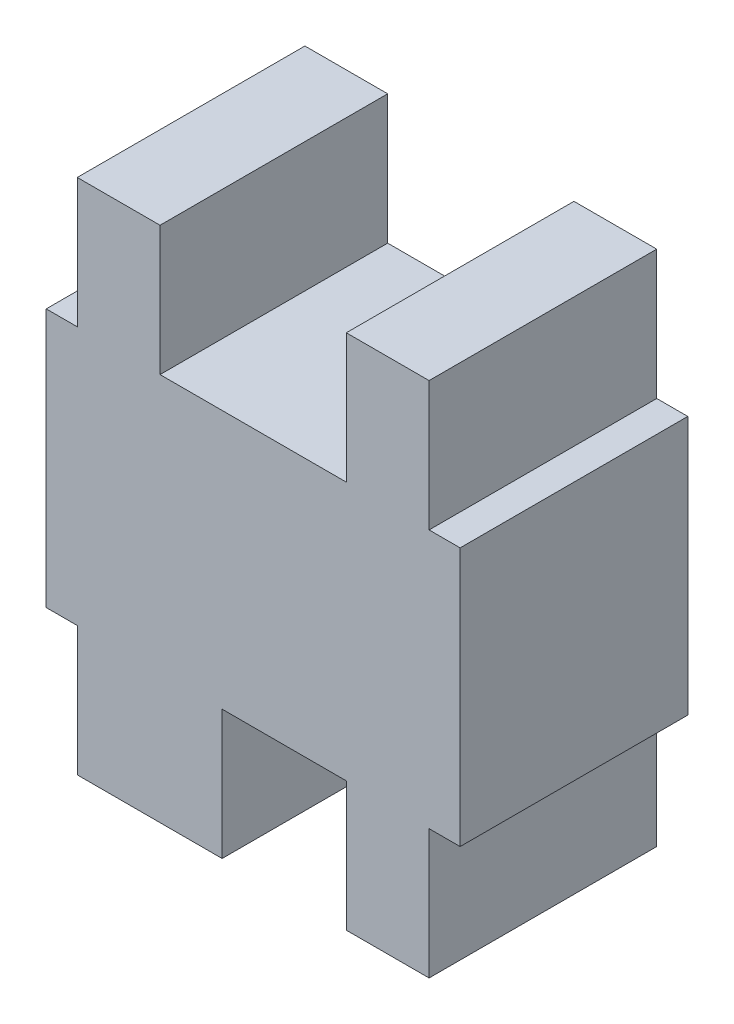
SolidWorks part; units mm, degrees
ref_plane "前视基准面" through (0, 0, 0) normal (0, 0, 1) x (1, 0, 0)
ref_plane "上视基准面" through (0, 0, 0) normal (0, 1, 0) x (1, 0, 0)
ref_plane "右视基准面" through (0, 0, 0) normal (1, 0, 0) x (0, 0, -1)
sketch "草图1" plane through (0, 0, 0) normal (0, 0, 1) x (1, 0, 0)
  line L0 (-1, 0.625) -> (-0.85, 0.625)
  line L1 (-0.85, 0.625) -> (-0.85, 1.25)
  line L2 (-0.85, 1.25) -> (-0.45, 1.25)
  line L3 (-0.45, 1.25) -> (-0.45, 0.625)
  line L4 (-0.45, 0.625) -> (0.45, 0.625)
  line L5 (0.45, 0.625) -> (0.45, 1.25)
  line L6 (0.45, 1.25) -> (0.85, 1.25)
  line L7 (0.85, 1.25) -> (0.85, 0.625)
  line L8 (0.85, 0.625) -> (1, 0.625)
  line L9 (1, 0.625) -> (1, -0.625)
  line L10 (1, -0.625) -> (0.85, -0.625)
  line L11 (0.85, -0.625) -> (0.85, -1.25)
  line L12 (0.85, -1.25) -> (0.45, -1.25)
  line L13 (0.45, -1.25) -> (0.45, -0.625)
  line L14 (0.45, -0.625) -> (-0.15, -0.625)
  line L15 (-0.15, -0.625) -> (-0.15, -1.25)
  line L16 (-0.15, -1.25) -> (-0.85, -1.25)
  line L17 (-0.85, -1.25) -> (-0.85, -0.625)
  line L18 (-0.85, -0.625) -> (-1, -0.625)
  line L19 (-1, -0.625) -> (-1, 0.625)
extrude "Component_Outline" add sketch "草图1" along normal blind 1.1 separate body
sketch3d "3D草图1"
  line L0 (0, 0, 0) -> (1, 0, 0)
  line L1 (0, 0, 0) -> (0, 1, 0)
  line L2 (0, 0, 0) -> (0, 0, 1)
  point P0 (0, 0, 0)
